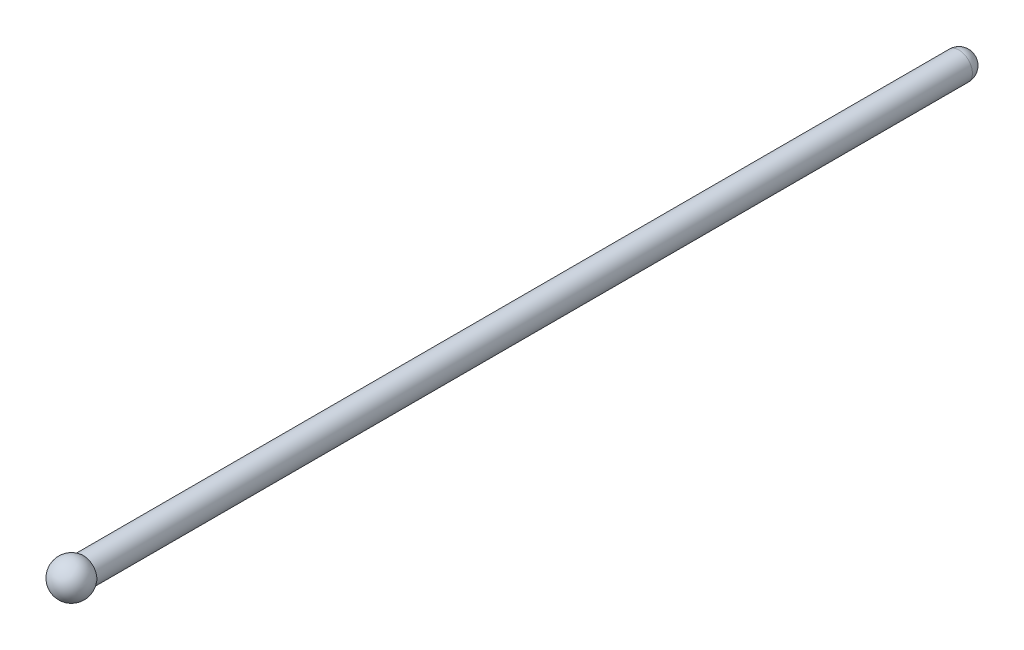
SolidWorks part; units mm, degrees
ref_plane "Front Plane" through (0, 0, 0) normal (0, 0, 1) x (1, 0, 0)
ref_plane "Top Plane" through (0, 0, 0) normal (0, 1, 0) x (1, 0, 0)
ref_plane "Right Plane" through (0, 0, 0) normal (1, 0, 0) x (0, 0, -1)
sketch "Sketch1" plane through (0, 0, 0) normal (0, 0, 1) x (1, 0, 0)
  circle A0 centre (0, 0) radius 0.75
  dimension "D1" = 1.5
extrude "Boss-Extrude1" add sketch "Sketch1" along normal blind 50
sketch "Sketch2" plane through (0, 0, 50) normal (0, 0, 1) x (1, 0, 0)
  line L0 (-1, 0) -> (1, 0)
  arc A0 (-1, 0) -> (1, 0) centre (0, 0) cw
  point P3 (0, 0)
  dimension "D1" = 2
revolve "Revolve1" add sketch "Sketch2" angle 360 about L0
fillet "Fillet1" radius 0.75 1 edges at (0.75, 0, 0)
